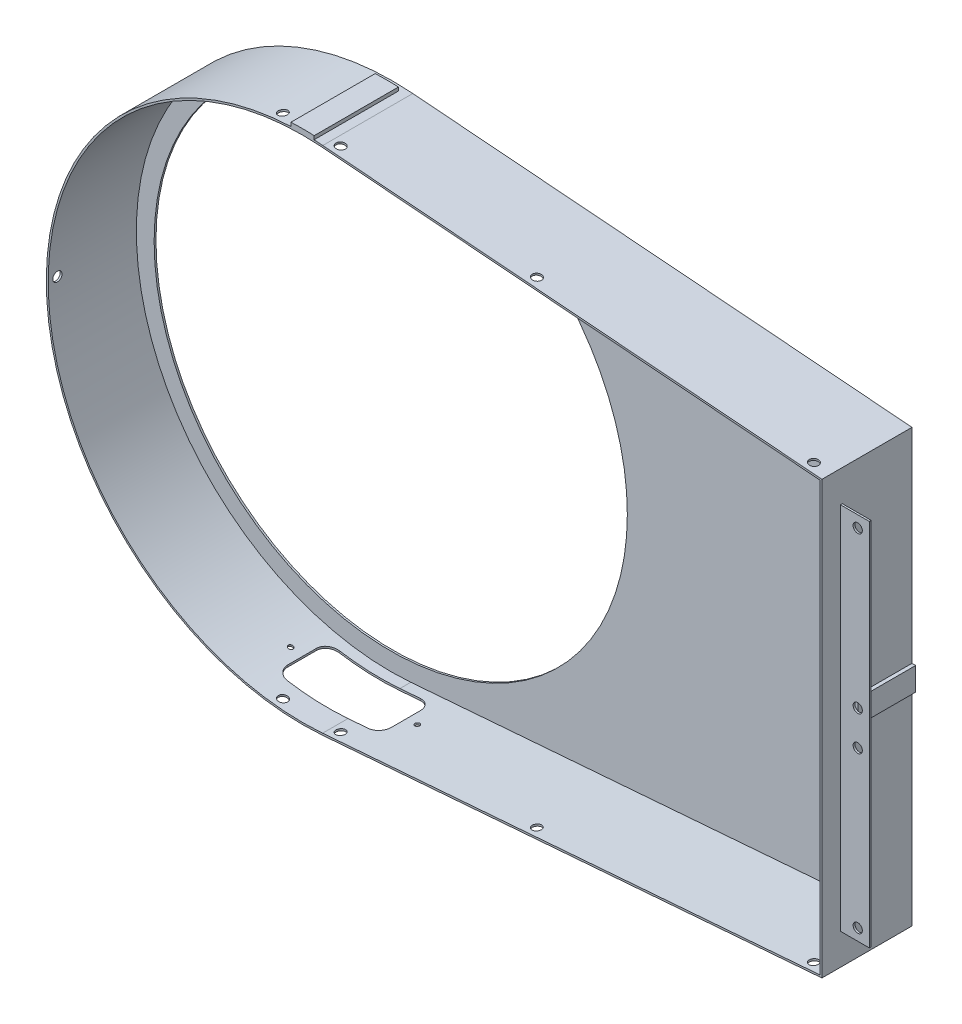
SolidWorks part; units mm, degrees
ref_plane "正面" through (0, 0, 0) normal (0, 0, 1) x (1, 0, 0)
ref_plane "平面" through (0, 0, 0) normal (0, 1, 0) x (1, 0, 0)
ref_plane "右側面" through (0, 0, 0) normal (1, 0, 0) x (0, 0, -1)
ref_plane "平面1" through (0, 0, 1.6) normal (0, 0, 1) x (1, 0, 0)
sketch "ｽｹｯﾁ1" plane through (0, 0, 1.6) normal (0, 0, 1) x (1, 0, 0)
  circle A0 centre (0, 0) radius 222
extrude "ﾎﾞｽ - 押し出し1" add sketch "ｽｹｯﾁ1" along normal blind 76.4
sketch "ｽｹｯﾁ2" plane through (0, 0, 1.6) normal (0, 0, 1) x (1, 0, 0)
  line L0 (17.5083, 221.3085) -> (450, 187.093)
  line L1 (450, 187.093) -> (450, -187.093)
  line L2 (450, -187.093) -> (17.5083, -221.3085)
  line L3 (17.5083, -221.3085) -> (17.5083, 221.3085)
extrude "ﾎﾞｽ - 押し出し2" add sketch "ｽｹｯﾁ2" along normal blind 76.4
sketch "ｽｹｯﾁ3" plane through (0, 0, 1.6) normal (0, 0, 1) x (1, 0, 0)
  circle A0 centre (0, 0) radius 220.4
extrude "ｶｯﾄ - 押し出し1" cut sketch "ｽｹｯﾁ3" against normal through all and the other way through all
sketch "ｽｹｯﾁ4" plane through (0, 0, 1.6) normal (0, 0, 1) x (1, 0, 0)
  line L0 (17.3821, 219.7135) -> (448.4, 185.6146)
  line L1 (448.4, 185.6146) -> (448.4, -185.6146)
  line L2 (448.4, -185.6146) -> (17.3821, -219.7135)
  line L3 (17.3821, -219.7135) -> (17.3821, 219.7135)
extrude "ｶｯﾄ - 押し出し2" cut sketch "ｽｹｯﾁ4" against normal through all and the other way through all
sketch "ｽｹｯﾁ5" plane through (0, 0, 0) normal (0, 0, 1) x (1, 0, 0)
  circle A0 centre (0, 0) radius 222
extrude "ﾎﾞｽ - 押し出し3" add sketch "ｽｹｯﾁ5" along normal blind 1.6
sketch "ｽｹｯﾁ6" plane through (0, 0, 0) normal (0, 0, 1) x (1, 0, 0)
  line L0 (17.5083, 221.3085) -> (450, 187.093)
  line L1 (450, 187.093) -> (450, -187.093)
  line L2 (450, -187.093) -> (17.5083, -221.3085)
  line L3 (17.5083, -221.3085) -> (17.5083, 221.3085)
extrude "ﾎﾞｽ - 押し出し4" add sketch "ｽｹｯﾁ6" along normal blind 1.6
sketch "ｽｹｯﾁ7" plane through (0, 0, 0) normal (0, 0, 1) x (1, 0, 0)
  circle A0 centre (0, 0) radius 205
extrude "ｶｯﾄ - 押し出し3" cut sketch "ｽｹｯﾁ7" against normal through all and the other way through all
ref_plane "平面2" through (0, 0, 60.4) normal (0, 0, 1) x (1, 0, 0)
sketch "ｽｹｯﾁ8" plane through (0, 0, 60.4) normal (0, 0, 1) x (1, 0, 0)
  line L0 (450, -160) -> (475, -160)
  line L1 (475, -160) -> (475, 160)
  line L2 (475, 160) -> (450, 160)
  line L3 (450, 160) -> (450, -160)
extrude "ﾎﾞｽ - 押し出し5" add sketch "ｽｹｯﾁ8" along normal blind 1.6
sketch "ｽｹｯﾁ9" plane through (0, 0, 0) normal (0, 0, 1) x (1, 0, 0)
  line L0 (450, -10) -> (453.2, -10)
  line L1 (453.2, -10) -> (453.2, 10)
  line L2 (453.2, 10) -> (450, 10)
  line L3 (450, 10) -> (450, -10)
extrude "ﾎﾞｽ - 押し出し6" add sketch "ｽｹｯﾁ9" along normal blind 50
ref_plane "平面3" through (0, 0, 5) normal (0, 0, 1) x (1, 0, 0)
sketch "ｽｹｯﾁ10" plane through (0, 0, 5) normal (0, 0, 1) x (1, 0, 0)
  line L0 (9.9251, 221.778) -> (10.0682, 224.9748)
  line L1 (-10.0682, 224.9748) -> (-9.9251, 221.778)
  arc A0 (10.0682, 224.9748) -> (-10.0682, 224.9748) centre (0, 0) ccw
  arc A1 (9.9251, 221.778) -> (-9.9251, 221.778) centre (0, 0) ccw
extrude "ﾎﾞｽ - 押し出し7" add sketch "ｽｹｯﾁ10" along normal blind 73
ref_plane "平面4" through (0, 0, 70) normal (0, 0, 1) x (1, 0, 0)
sketch "ｽｹｯﾁ11" plane through (0, 0, 70) normal (0, 0, 1) x (1, 0, 0)
  line L0 (-22.7396, 199.9109) -> (-27.2604, 239.6546)
  line L1 (-27.2604, 239.6546) -> (-31.2348, 239.2025)
  line L2 (-31.2348, 239.2025) -> (-26.714, 199.4588)
  line L3 (-26.714, 199.4588) -> (-22.7396, 199.9109)
  line L4 (-22.7396, 199.9109) -> (-27.2604, 239.6546) construction
revolve "ｶｯﾄ - 回転1" cut sketch "ｽｹｯﾁ11" angle 360 about L4
sketch "ｽｹｯﾁ12" plane through (0, 0, 70) normal (0, 0, 1) x (1, 0, 0)
  line L0 (23.4227, 199.9756) -> (26.5773, 239.851)
  line L1 (26.5773, 239.851) -> (22.5898, 240.1665)
  line L2 (22.5898, 240.1665) -> (19.4351, 200.2911)
  line L3 (19.4351, 200.2911) -> (23.4227, 199.9756)
  line L4 (23.4227, 199.9756) -> (26.5773, 239.851) construction
revolve "ｶｯﾄ - 回転2" cut sketch "ｽｹｯﾁ12" angle 360 about L4
sketch "ｽｹｯﾁ13" plane through (0, 0, 70) normal (0, 0, 1) x (1, 0, 0)
  line L0 (193.4227, 186.5265) -> (196.5773, 226.4019)
  line L1 (196.5773, 226.4019) -> (192.5898, 226.7174)
  line L2 (192.5898, 226.7174) -> (189.4351, 186.8419)
  line L3 (189.4351, 186.8419) -> (193.4227, 186.5265)
  line L4 (193.4227, 186.5265) -> (196.5773, 226.4019) construction
revolve "ｶｯﾄ - 回転3" cut sketch "ｽｹｯﾁ13" angle 360 about L4
sketch "ｽｹｯﾁ14" plane through (0, 0, 70) normal (0, 0, 1) x (1, 0, 0)
  line L0 (433.4227, 167.5395) -> (436.5773, 207.4149)
  line L1 (436.5773, 207.4149) -> (432.5898, 207.7303)
  line L2 (432.5898, 207.7303) -> (429.4351, 167.8549)
  line L3 (429.4351, 167.8549) -> (433.4227, 167.5395)
  line L4 (433.4227, 167.5395) -> (436.5773, 207.4149) construction
revolve "ｶｯﾄ - 回転4" cut sketch "ｽｹｯﾁ14" angle 360 about L4
sketch "ｽｹｯﾁ15" plane through (0, 0, 70) normal (0, 0, 1) x (1, 0, 0)
  line L0 (-22.7396, -199.9109) -> (-27.2604, -239.6546)
  line L1 (-27.2604, -239.6546) -> (-23.286, -240.1066)
  line L2 (-23.286, -240.1066) -> (-18.7652, -200.3629)
  line L3 (-18.7652, -200.3629) -> (-22.7396, -199.9109)
  line L4 (-22.7396, -199.9109) -> (-27.2604, -239.6546) construction
revolve "ｶｯﾄ - 回転5" cut sketch "ｽｹｯﾁ15" angle 360 about L4
sketch "ｽｹｯﾁ16" plane through (0, 0, 70) normal (0, 0, 1) x (1, 0, 0)
  line L0 (23.4227, -199.9756) -> (26.5773, -239.851)
  line L1 (26.5773, -239.851) -> (30.5649, -239.5356)
  line L2 (30.5649, -239.5356) -> (27.4102, -199.6602)
  line L3 (27.4102, -199.6602) -> (23.4227, -199.9756)
  line L4 (23.4227, -199.9756) -> (26.5773, -239.851) construction
revolve "ｶｯﾄ - 回転6" cut sketch "ｽｹｯﾁ16" angle 360 about L4
sketch "ｽｹｯﾁ17" plane through (0, 0, 70) normal (0, 0, 1) x (1, 0, 0)
  line L0 (193.4227, -186.5265) -> (196.5773, -226.4019)
  line L1 (196.5773, -226.4019) -> (200.5649, -226.0864)
  line L2 (200.5649, -226.0864) -> (197.4102, -186.211)
  line L3 (197.4102, -186.211) -> (193.4227, -186.5265)
  line L4 (193.4227, -186.5265) -> (196.5773, -226.4019) construction
revolve "ｶｯﾄ - 回転7" cut sketch "ｽｹｯﾁ17" angle 360 about L4
sketch "ｽｹｯﾁ18" plane through (0, 0, 70) normal (0, 0, 1) x (1, 0, 0)
  line L0 (433.4227, -167.5395) -> (436.5773, -207.4149)
  line L1 (436.5773, -207.4149) -> (440.5649, -207.0994)
  line L2 (440.5649, -207.0994) -> (437.4102, -167.224)
  line L3 (437.4102, -167.224) -> (433.4227, -167.5395)
  line L4 (433.4227, -167.5395) -> (436.5773, -207.4149) construction
revolve "ｶｯﾄ - 回転8" cut sketch "ｽｹｯﾁ18" angle 360 about L4
sketch "ｽｹｯﾁ19" plane through (0, 0, 70) normal (0, 0, 1) x (1, 0, 0)
  line L0 (-201.2, 0) -> (-241.2, 0)
  line L1 (-241.2, 0) -> (-241.2, -4)
  line L2 (-241.2, -4) -> (-201.2, -4)
  line L3 (-201.2, -4) -> (-201.2, 0)
  line L4 (-201.2, 0) -> (-241.2, 0) construction
revolve "ｶｯﾄ - 回転9" cut sketch "ｽｹｯﾁ19" angle 360 about L4
sketch "ｽｹｯﾁ20" plane through (0, 0, 0) normal (0, 0, 1) x (1, 0, 0)
  circle A0 centre (465, -150) radius 4
  circle A1 centre (465, -15) radius 4
  circle A2 centre (465, 15) radius 4
  circle A3 centre (465, 150) radius 4
sketch "ｽｹｯﾁ21" plane through (0, 0, 0) normal (0, 0, 1) x (1, 0, 0)
  circle A0 centre (465, -150) radius 4
  circle A1 centre (465, -15) radius 4
  circle A2 centre (465, 15) radius 4
  circle A3 centre (465, 150) radius 4
extrude "ｶｯﾄ - 押し出し5" cut sketch "ｽｹｯﾁ21" along normal blind 62
sketch "ｽｹｯﾁ22" plane through (0, 0, 0) normal (0, 1, 0) x (1, 0, 0)
  line L0 (-35, -56) -> (35, -56)
  line L1 (45, -46) -> (45, -21)
  line L2 (35, -11) -> (-35, -11)
  line L3 (-45, -21) -> (-45, -46)
  arc A0 (35, -56) -> (45, -46) centre (35, -46) ccw
  arc A1 (45, -21) -> (35, -11) centre (35, -21) ccw
  arc A2 (-35, -11) -> (-45, -21) centre (-35, -21) ccw
  arc A3 (-45, -46) -> (-35, -56) centre (-35, -46) ccw
extrude "ｶｯﾄ - 押し出し6" cut sketch "ｽｹｯﾁ22" against normal blind 240
ref_plane "平面5" through (0, 0, 33.5) normal (0, 0, 1) x (1, 0, 0)
sketch "ｽｹｯﾁ23" plane through (0, 0, 33.5) normal (0, 0, 1) x (1, 0, 0)
  line L0 (-50.0271, -194.8813) -> (-59.9729, -233.6251)
  line L1 (-59.9729, -233.6251) -> (-57.9388, -234.1473)
  line L2 (-57.9388, -234.1473) -> (-47.9931, -195.4035)
  line L3 (-47.9931, -195.4035) -> (-50.0271, -194.8813)
  line L4 (-50.0271, -194.8813) -> (-59.9729, -233.6251) construction
revolve "ｶｯﾄ - 回転10" cut sketch "ｽｹｯﾁ23" angle 360 about L4
sketch "ｽｹｯﾁ24" plane through (0, 0, 33.5) normal (0, 0, 1) x (1, 0, 0)
  line L0 (53.4227, -197.6022) -> (56.5773, -237.4777)
  line L1 (56.5773, -237.4777) -> (58.6708, -237.312)
  line L2 (58.6708, -237.312) -> (55.5161, -197.4366)
  line L3 (55.5161, -197.4366) -> (53.4227, -197.6022)
  line L4 (53.4227, -197.6022) -> (56.5773, -237.4777) construction
revolve "ｶｯﾄ - 回転11" cut sketch "ｽｹｯﾁ24" angle 360 about L4
